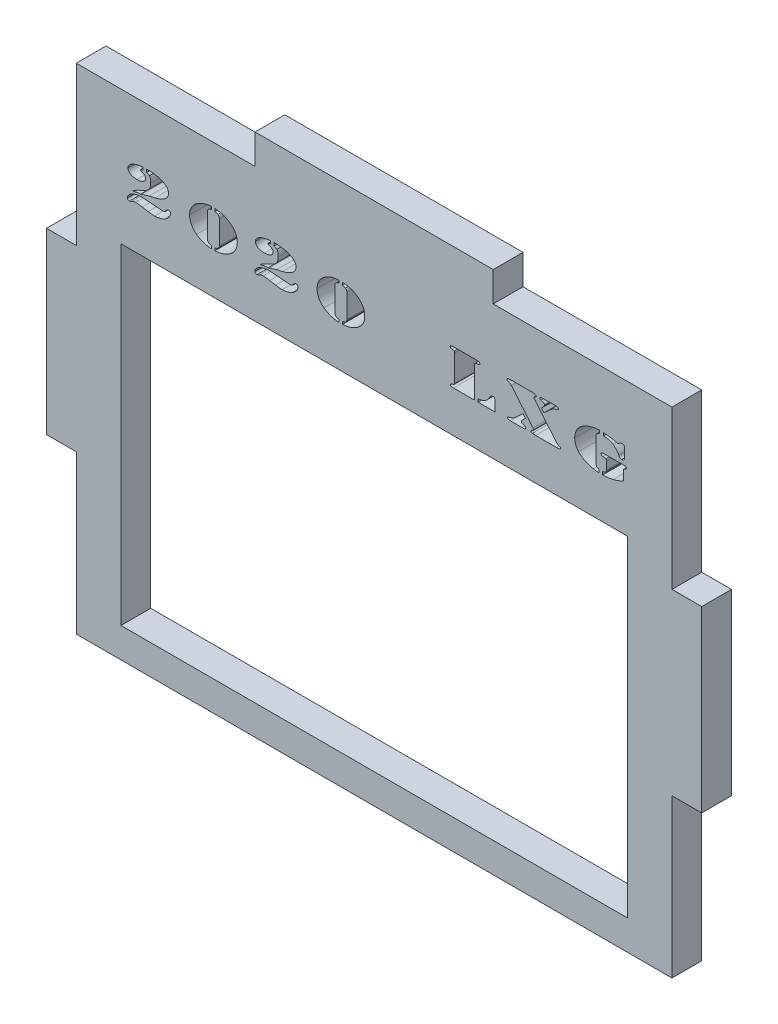
SolidWorks part; units mm, degrees
ref_plane "前视基准面" through (0, 0, 0) normal (0, 0, 1) x (1, 0, 0)
ref_plane "上视基准面" through (0, 0, 0) normal (0, 1, 0) x (1, 0, 0)
ref_plane "右视基准面" through (0, 0, 0) normal (1, 0, 0) x (0, 0, -1)
sketch "草图1" plane through (0, 0, 0) normal (0, 0, 1) x (1, 0, 0)
  line L0 (0, 56.5) -> (0, 83)
  line L1 (0, 0) -> (100, 0)
  line L2 (0, 0) -> (0, 26.5)
  line L3 (0, 83) -> (30, 83)
  line L4 (100, 0) -> (100, 26.5)
  line L5 (0, 56.5) -> (-5, 56.5)
  line L7 (0, 26.5) -> (-5, 26.5)
  line L8 (-5, 56.5) -> (-5, 26.5)
  line L9 (100, 56.5) -> (105, 56.5)
  line L11 (100, 26.5) -> (105, 26.5)
  line L12 (105, 56.5) -> (105, 26.5)
  line L14 (30, 83) -> (30, 88)
  line L15 (30, 88) -> (70, 88)
  line L16 (70, 83) -> (70, 88)
  line L17 (7.5, 60.5) -> (92.5, 60.5)
  line L18 (7.5, 60.5) -> (7.5, 5)
  line L19 (7.5, 5) -> (92.5, 5)
  line L20 (92.5, 60.5) -> (92.5, 5)
  line L21 (70, 83) -> (100, 83)
  line L22 (100, 56.5) -> (100, 83)
  text T0 "2020  LXG" font "Stencil" height 6
  point P22 (4.5669, 30.3414)
  dimension "D1" = 100
  dimension "D2" = 83
  dimension "D3" = 30
  dimension "D4" = 5
  dimension "D5" = 26.5
  dimension "D6" = 30
  dimension "D7" = 5
  dimension "D8" = 26.5
  dimension "D9" = 40
  dimension "D10" = 5
  dimension "D11" = 30
  dimension "D12" = 85
  dimension "D13" = 55.5
  dimension "D14" = 5
  dimension "D15" = 7.5
extrude "凸台-拉伸1" add sketch "草图1" along normal blind 5
